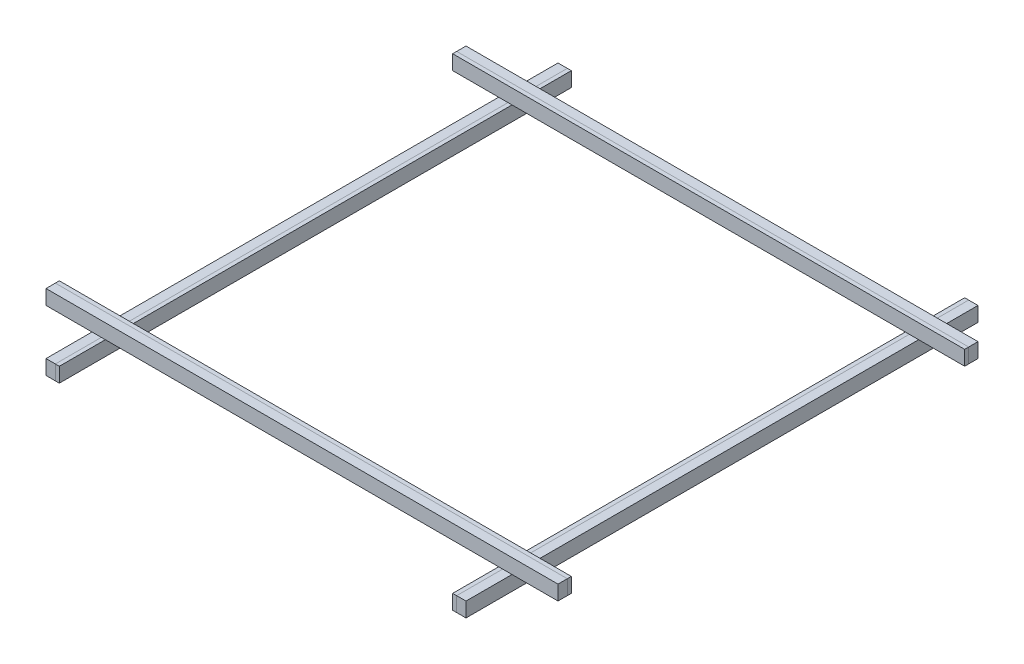
SolidWorks part; units mm, degrees
material "Doug Fir"
ref_plane "Front Plane" through (0, 0, 0) normal (0, 0, 1) x (1, 0, 0)
ref_plane "Top Plane" through (0, 0, 0) normal (0, 1, 0) x (1, 0, 0)
ref_plane "Right Plane" through (0, 0, 0) normal (1, 0, 0) x (0, 0, -1)
sketch "Lower Level" plane through (0, 0, 0) normal (0, 1, 0) x (1, 0, 0)
  line L0 (177.8, 0) -> (177.8, 4876.8)
  line L1 (4089.4, 0) -> (4089.4, 4876.8)
  line L2 (177.8, 2438.4) -> (4089.4, 2438.4) construction
  point P7 (2133.6, 2438.4)
  dimension "D1" = 4876.8
  dimension "D2" = 1955.8
ref_plane "Plane2" through (0, 139.7, 0) normal (0, 1, 0) x (1, 0, 0)
sketch "Sketch12" plane through (0, 139.7, 0) normal (0, 1, 0) x (1, 0, 0)
  line L0 (-304.8, 4394.2) -> (4572, 4394.2)
  line L1 (4572, 482.6) -> (-304.8, 482.6)
  line L2 (2133.6, 4394.2) -> (2133.6, 482.6) construction
  point P0 (2133.6, 2438.4)
  point P6 (2133.6, 482.6)
  point P7 (2133.6, 4394.2)
  point P10 (2133.6, 2438.4)
  dimension "D1" = 4876.8
  dimension "D2" = 1955.8
other "Profiles 4X6(1)"
ref_plane "Plane1" through (177.8, 0, 0) normal (0, 0, -1) x (-1, 0, 0)
sketch "Sketch1" plane through (177.8, 0, 0) normal (0, 0, -1) x (-1, 0, 0)
  line L1 (-44.45, 69.85) -> (44.45, 69.85)
  line L2 (-44.45, 69.85) -> (-44.45, -69.85)
  line L3 (-44.45, -69.85) -> (44.45, -69.85)
  line L4 (44.45, 69.85) -> (44.45, -69.85)
  line L5 (-44.45, 69.85) -> (44.45, -69.85) construction
  line L6 (-44.45, -69.85) -> (44.45, 69.85) construction
  point P0 (0, 0)
  point P6 (0, 69.85)
  point P7 (0, -69.85)
  point P8 (44.45, 0)
  point P9 (-44.45, 0)
  point P10 (0, 0)
  dimension "D1" = 88.9
  dimension "D2" = 139.7
sketch3d "3DSketch2"
  line L0 (2133.6, 139.7, -2438.4) -> (2133.6, 0, -2438.4)
  line L1 (177.8, 0, -2438.4) -> (4089.4, 0, -2438.4) construction
sketch "Sketch13" plane through (-304.8, 0, 0) normal (-1, 0, 0) x (0, 0, 1)
  line L1 (-4349.75, 209.55) -> (-4311.65, 209.55)
  line L2 (-4349.75, 209.55) -> (-4349.75, 69.85)
  line L3 (-4349.75, 69.85) -> (-4311.65, 69.85)
  line L4 (-4311.65, 209.55) -> (-4311.65, 69.85)
  line L5 (-527.05, 209.55) -> (-565.15, 209.55)
  line L6 (-527.05, 209.55) -> (-527.05, 69.85)
  line L7 (-527.05, 69.85) -> (-565.15, 69.85)
  line L8 (-565.15, 209.55) -> (-565.15, 69.85)
  dimension "D1" = 38.1
  dimension "D2" = 139.7
  dimension "D3" = 38.1
extrude "Boss-Extrude1" add sketch "Sketch13" against normal up to surface (4876.8 mm away) separate body up to face at (4572, 139.7, -482.6)
sketch "Sketch14" plane through (0, 0, 0) normal (0, 0, 1) x (1, 0, 0)
  line L0 (4572, 69.85) -> (-304.8, 69.85) construction
  line L1 (222.25, -69.85) -> (260.35, -69.85)
  line L2 (222.25, -69.85) -> (222.25, 69.85)
  line L3 (222.25, 69.85) -> (260.35, 69.85)
  line L4 (260.35, -69.85) -> (260.35, 69.85)
  line L6 (4044.95, -69.85) -> (4006.85, -69.85)
  line L7 (4044.95, -69.85) -> (4044.95, 69.85)
  line L8 (4044.95, 69.85) -> (4006.85, 69.85)
  line L9 (4006.85, -69.85) -> (4006.85, 69.85)
  dimension "D1" = 38.1
  dimension "D2" = 38.1
extrude "Boss-Extrude2" add sketch "Sketch14" against normal up to surface (4876.8 mm away) separate body up to face at (4089.4, 0, -4876.8)
equation "\"Width\" = 77"
equation "\"Length\"=192"
equation "\"D1@Lower Level\"=\"Length\""
equation "\"D2@Lower Level\"=\"Width\""
equation "\"D1@Sketch12\"=\"Length\""
equation "\"D2@Sketch12\"=\"Width\""
